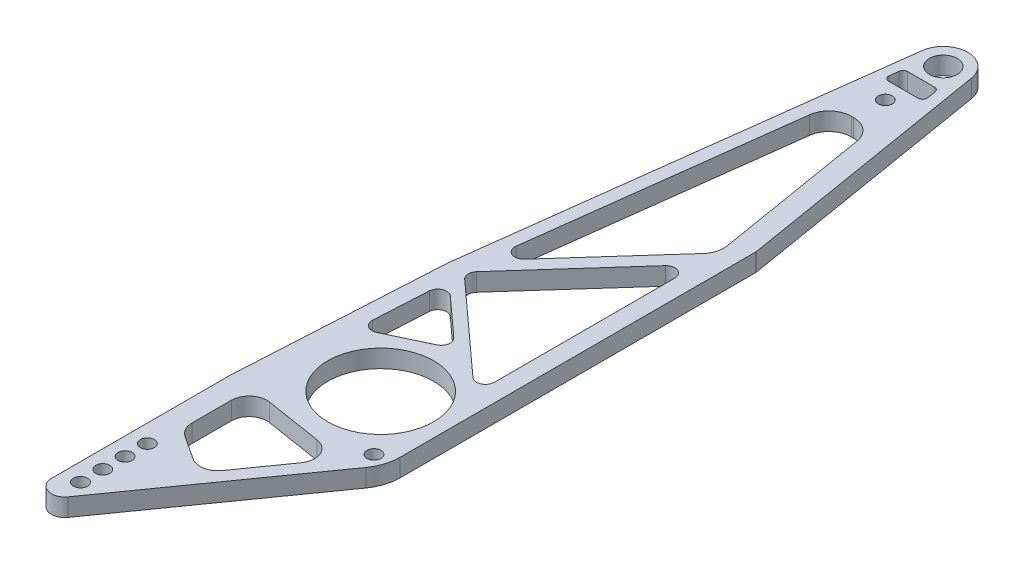
SolidWorks part; units mm, degrees
material "6061-T6 (SS)"
ref_plane "X-Y Datum" through (0, 0, 0) normal (0, 0, 1) x (1, 0, 0)
ref_plane "X-Z Datum" through (0, 0, 0) normal (0, 1, 0) x (1, 0, 0)
ref_plane "Y-Z Datum" through (0, 0, 0) normal (1, 0, 0) x (0, 0, -1)
other "Graphic1" [suppressed]
other "Graphic (Closed) -1" [suppressed]
sketch "Sketch1" plane through (0, 0, 0) normal (0, 1, 0) x (1, 0, 0)
  line L0 (25.4, -82.7357) -> (25.4, -202.7088)
  line L2 (-25.4, -229.1053) -> (-25.4, -131.2787)
  line L6 (25.4, -160.2465) -> (-25.4, -160.2465) construction
  line L28 (22.225, -208.2081) -> (-19.685, -232.4048)
  line L29 (0, 0) -> (41.91, 0) construction
  line L30 (41.91, 0) -> (0, -160.2465) construction
  line L31 (0, -160.2465) -> (0, 0) construction
  line L32 (-20.32, -219.075) -> (-20.32, -212.725) construction
  line L33 (25.2486, -81.3572) -> (6.8184, 1.5163)
  line L34 (-25.4, -131.2787) -> (-6.9178, 0.9668)
  circle A0 centre (0, 0) radius 3.9688
  circle A2 centre (0, -160.2465) radius 15.0813
  circle A6 centre (-20.32, -225.425) radius 2
  circle A7 centre (-20.32, -219.075) radius 2
  circle A8 centre (-20.32, -212.725) radius 2
  circle A9 centre (-20.32, -206.375) radius 2
  arc A10 (6.8184, 1.5163) -> (-6.9178, 0.9668) centre (0, 0) ccw
  circle A41 centre (0, -16.51) radius 2
  arc A42 (-25.4, -229.1053) -> (-19.685, -232.4048) centre (-21.59, -229.1053) ccw
  arc A43 (25.4, -202.7088) -> (22.225, -208.2081) centre (19.05, -202.7088) cw
  circle A45 centre (21.59, -82.0382) radius 2 construction
  arc A46 (25.2486, -81.3572) -> (25.4, -82.7357) centre (19.05, -82.7357) cw
  point P21 (-20.32, -215.9)
  point P30 (25.4, -206.375)
  point P51 (25.4, -82.0382)
  dimension "D1" = 7.9375
  dimension "D4" = 30.1625
  dimension "D8" = 4
  dimension "D6" = 6.985
  dimension "D65" = 4
  dimension "D18" = 3.81
  dimension "D20" = 6.35
  dimension "D32" = 4
  dimension "D34" = 6.35
  dimension "D9" = 5.08
  dimension "D11" = 6.35
  dimension "D12" = 6.35
  dimension "D13" = 6.35
  dimension "D5" = 50.8
  dimension "D66" = 16.51
  dimension "D2" = 41.91
  dimension "D3" = 165.6363
  dimension "D7" = 215.9
  dimension "D10" = 120
  dimension "D19" = 206.375
  dimension "D23" = 187.956
  dimension "D33" = 3.81
extrude "Boss-Extrude1" [suppressed] add sketch "Sketch1" against normal blind 6.35
sketch "Sketch9" [suppressed] plane through (0, 0, 0) normal (0, 1, 0) x (1, 0, 0)
  line L0 (0, 0) -> (0, -162.7876)
  line L1 (0, -162.7876) -> (41.91, 0)
  line L2 (41.91, 0) -> (0, 0)
  line L3 (0, 0) -> (39.3048, -10.1191) construction
  dimension "D1" = 168.096
  dimension "D2" = 0
  dimension "D3" = 41.91
  dimension "D4" = 40.5865
  dimension "D5" = 75.563
  dimension "D6" = 162.7876
sketch "Sketch4" [suppressed] plane through (0, 0, 0) normal (0, 1, 0) x (1, 0, 0)
  line L0 (0, -34.29) -> (0, 0)
  line L1 (0, 0) -> (152.4, 0)
  line L2 (152.4, 0) -> (0, -34.29)
  line L3 (0, 0) -> (7.3435, -32.6377) construction
  dimension "D1" = 12.68
  dimension "D2" = 156.21
  dimension "D3" = 34.29
  dimension "D4" = 152.4
  dimension "D5" = 33.4537
sketch "Sketch10" [suppressed] plane through (-25.4, 0, 0) normal (-1, 0, 0) x (0, 0, 1)
  line L0 (197.3553, 0) -> (197.3553, -6.35)
  line L1 (131.2787, 0) -> (229.1053, 0) construction
  line L2 (131.2787, -6.35) -> (229.1053, -6.35) construction
  line L5 (229.1053, -6.35) -> (229.1053, 0) construction
  dimension "D1" = 31.75
split line "Split Line1" [suppressed]
other "Graphic2" [suppressed]
other "Graphic (Closed) -2" [suppressed]
sketch "Sketch11" plane through (0, 0, 0) normal (0, 1, 0) x (1, 0, 0)
  line L2 (19.05, -173.7588) -> (19.05, -72.5986)
  line L3 (16.7146, -181.0981) -> (-18.4806, -230.8018)
  line L4 (0, 0) -> (41.91, 0) construction
  line L7 (-20.32, -219.075) -> (-20.32, -212.725) construction
  line L8 (19.016, -72.1842) -> (6.8914, 1.1395)
  line L10 (11.9403, -80.3341) -> (-12.0906, -107.1852)
  line L11 (-16.5032, -105.1725) -> (-7.1155, -30.9532)
  line L12 (13.4735, -75.0634) -> (6.14, -30.7141)
  line L14 (13.97, -141.8125) -> (13.97, -90.4261)
  line L15 (9.5373, -88.7321) -> (-15.8435, -117.0916)
  line L16 (-15.6576, -120.6667) -> (9.7233, -143.6937)
  line L18 (-13.5825, -126.8362) -> (-2.8095, -136.6101)
  line L23 (-25.4, -228.6) -> (-25.4, -177.8714)
  line L24 (19.05, -72.39) -> (13.97, -78.0662) construction
  line L25 (6.2822, -189.2382) -> (-3.0189, -202.3734)
  line L27 (-17.8252, -128.5747) -> (-18.6861, -143.8712)
  line L29 (-0.1249, -25.4) -> (-0.8157, -25.4)
  line L30 (3.8345, -6.35) -> (-3.8345, -6.35)
  line L31 (-5.0945, -7.4606) -> (-5.4157, -10.0006)
  line L32 (-4.1558, -11.43) -> (4.2545, -11.43)
  line L33 (5.5075, -9.9528) -> (5.0875, -7.4128)
  line L34 (-6.9298, 0.8765) -> (-22.089, -118.9715)
  line L35 (-22.089, -118.9715) -> (-25.396, -177.7287)
  line L36 (-3.427, -140.7859) -> (-15.0609, -146.3085)
  line L37 (2.9318, -181.2851) -> (-13.1745, -178.7315)
  line L39 (-19.05, -194.9719) -> (-19.05, -183.7489)
  line L40 (-9.9519, -203.6849) -> (-16.7571, -199.2191)
  circle A0 centre (0, 0) radius 3.9687
  circle A1 centre (0, -160.2465) radius 15.0813
  circle A2 centre (-20.32, -225.425) radius 2
  circle A3 centre (-20.32, -219.075) radius 2
  circle A4 centre (-20.32, -212.725) radius 2
  circle A5 centre (-20.32, -206.375) radius 2
  arc A6 (6.8914, 1.1395) -> (-6.9298, 0.8765) centre (0, 0) ccw
  circle A7 centre (0, -16.51) radius 2
  arc A8 (-25.4, -228.6) -> (-18.4806, -230.8018) centre (-21.59, -228.6) ccw
  arc A15 (-7.1155, -30.9532) -> (-0.8157, -25.4) centre (-0.8157, -31.75) cw
  arc A16 (-0.1249, -25.4) -> (6.14, -30.7141) centre (-0.1249, -31.75) cw
  arc A17 (-5.4157, -10.0006) -> (-4.1558, -11.43) centre (-4.1558, -10.16) ccw
  arc A18 (-5.0945, -7.4606) -> (-3.8345, -6.35) centre (-3.8345, -7.62) cw
  arc A19 (3.8345, -6.35) -> (5.0875, -7.4128) centre (3.8345, -7.62) cw
  arc A20 (5.5075, -9.9528) -> (4.2545, -11.43) centre (4.2545, -10.16) cw
  arc A21 (2.9318, -181.2851) -> (6.2822, -189.2382) centre (2.1363, -186.3025) cw
  arc A22 (-19.05, -183.7489) -> (-13.1745, -178.7315) centre (-13.97, -183.7489) cw
  arc A23 (-19.05, -194.9719) -> (-16.7571, -199.2191) centre (-13.97, -194.9719) ccw
  arc A24 (-9.9519, -203.6849) -> (-3.0189, -202.3734) centre (-7.1648, -199.4377) ccw
  arc A25 (-16.5032, -105.1725) -> (-12.0906, -107.1852) centre (-13.9833, -105.4913) ccw
  arc A26 (11.9403, -80.3341) -> (13.4735, -75.0634) centre (7.2085, -76.0993) ccw
  arc A27 (-18.6861, -143.8712) -> (-15.0609, -146.3085) centre (-16.1501, -144.0139) ccw
  arc A28 (-17.8252, -128.5747) -> (-13.5825, -126.8362) centre (-15.2892, -128.7174) cw
  arc A29 (-2.8095, -136.6101) -> (-3.427, -140.7859) centre (-4.5162, -138.4913) cw
  arc A30 (-15.8435, -117.0916) -> (-15.6576, -120.6667) centre (-13.9509, -118.7855) ccw
  arc A31 (9.7233, -143.6937) -> (13.97, -141.8125) centre (11.43, -141.8125) ccw
  arc A32 (9.5373, -88.7321) -> (13.97, -90.4261) centre (11.43, -90.4261) cw
  arc A33 (19.016, -72.1842) -> (19.05, -72.5986) centre (16.51, -72.5986) cw
  arc A34 (-25.396, -177.7287) -> (-25.4, -177.8714) centre (-22.86, -177.8714) ccw
  arc A35 (19.05, -173.7588) -> (16.7146, -181.0981) centre (6.35, -173.7588) cw
  circle A36 centre (14.605, -176.7565) radius 2
  point P16 (-20.32, -215.9)
  point P60 (0, -6.35)
  point P66 (-19.05, -177.8)
  point P71 (-5.8525, -206.375)
  point P74 (-17.526, -113.2584)
  point P82 (-17.526, -123.2585)
  point P85 (0, -139.1591)
  point P88 (-17.526, -118.9715)
  point P91 (13.97, -147.5465)
  point P94 (13.97, -83.7792)
  point P100 (-25.4, -177.8)
  point P103 (19.05, -177.8)
  dimension "D1" = 7.9375
  dimension "D2" = 30.1625
  dimension "D3" = 4
  dimension "D9" = 6.985
  dimension "D10" = 4
  dimension "D16" = 3.81
  dimension "D17" = 3.81
  dimension "D19" = 6.35
  dimension "D20" = 19.05
  dimension "D26" = 50.8
  dimension "D27" = 6.35
  dimension "D28" = 8.89
  dimension "D30" = 3.81
  dimension "D35" = 1.27
  dimension "D38" = 5.08
  dimension "D39" = 2.54
  dimension "D40" = 2.54
  dimension "D41" = 2.54
  dimension "D42" = 6.35
  dimension "D43" = 12.7
  dimension "D44" = 4
  dimension "D4" = 5.08
  dimension "D5" = 6.35
  dimension "D6" = 6.35
  dimension "D7" = 6.35
  dimension "D8" = 228.6
  dimension "D11" = 16.51
  dimension "D12" = 41.91
  dimension "D13" = 160.2465
  dimension "D14" = 215.9
  dimension "D15" = 21.59
  dimension "D18" = 17.526
  dimension "D21" = 72.39
  dimension "D22" = 5.08
  dimension "D23" = 3.81
  dimension "D24" = 41.275
  dimension "D25" = 12.7
  dimension "D29" = 3.175
  dimension "D31" = 5.08
  dimension "D32" = 6.35
  dimension "D33" = 3.175
  dimension "D34" = 19.05
  dimension "D36" = 20.32
  dimension "D37" = 7.9375
  dimension "D45" = 14.605
  dimension "D46" = 16.51
extrude "Boss-Extrude2" add sketch "Sketch11" against normal blind 5.08
sketch "Sketch13" plane through (-25.4, 0, 0) normal (-1, 0, 0) x (0, 0, 1)
  line L0 (196.85, 0) -> (196.85, -5.08)
  line L1 (177.8714, 0) -> (228.6, 0) construction
  line L2 (177.8714, -5.08) -> (228.6, -5.08) construction
  line L3 (228.6, -5.08) -> (228.6, 0) construction
  dimension "D1" = 31.75
split line "Split Line3"
equation "\"toePadMount\"=0.25"
equation "\"D11@Sketch1\"=\"toePadMount\""
equation "\"D12@Sketch1\"=\"toePadMount\""
equation "\"D13@Sketch1\"=\"toePadMount\""
